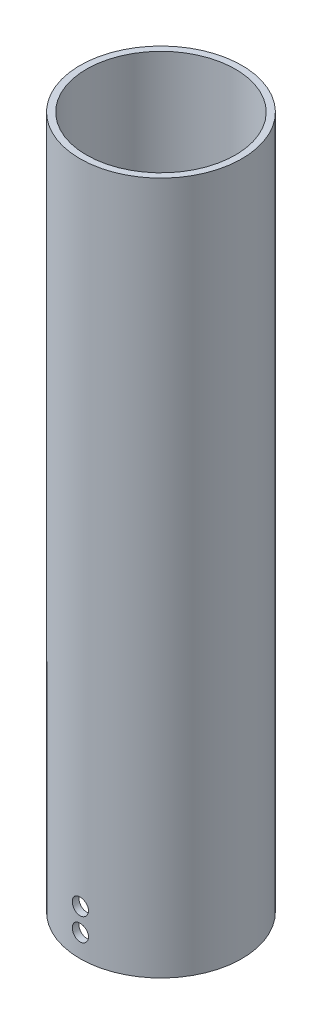
SolidWorks part; units mm, degrees
material "ПВХ 0.007 Смягченный"
ref_plane "Спереди" through (0, 0, 0) normal (0, 0, 1) x (1, 0, 0)
ref_plane "Сверху" through (0, 0, 0) normal (0, 1, 0) x (1, 0, 0)
ref_plane "Справа" through (0, 0, 0) normal (1, 0, 0) x (0, 0, -1)
sketch "Эскиз1" plane through (0, 0, 0) normal (0, 1, 0) x (1, 0, 0)
  circle A0 centre (0, 0) radius 25
  circle A1 centre (0, 0) radius 23
  dimension "ExDBody" = 50
  dimension "InDBody" = 46
extrude "Бобышка-Вытянуть1" add sketch "Эскиз1" along normal blind 214
sketch "Эскиз2" plane through (0, 0, 0) normal (0, 0, 1) x (1, 0, 0)
  line L0 (-25, 0) -> (-25, 20) construction
  line L1 (-25, 214) -> (-25, 0) construction
  line L2 (-25, 20) -> (41.185, 20) construction
  line L3 (-25, 7) -> (-25, 27) construction
  line L4 (-25, 0) -> (25, 0) construction
  circle A0 centre (0, 7) radius 2.5
  circle A1 centre (0, 14) radius 2.5
  dimension "D2" = 5
  dimension "D1" = 20
  dimension "D4" = 7
  dimension "D3" = 2
extrude "Вырез-Вытянуть1" cut sketch "Эскиз2" against normal through all and the other way through all
